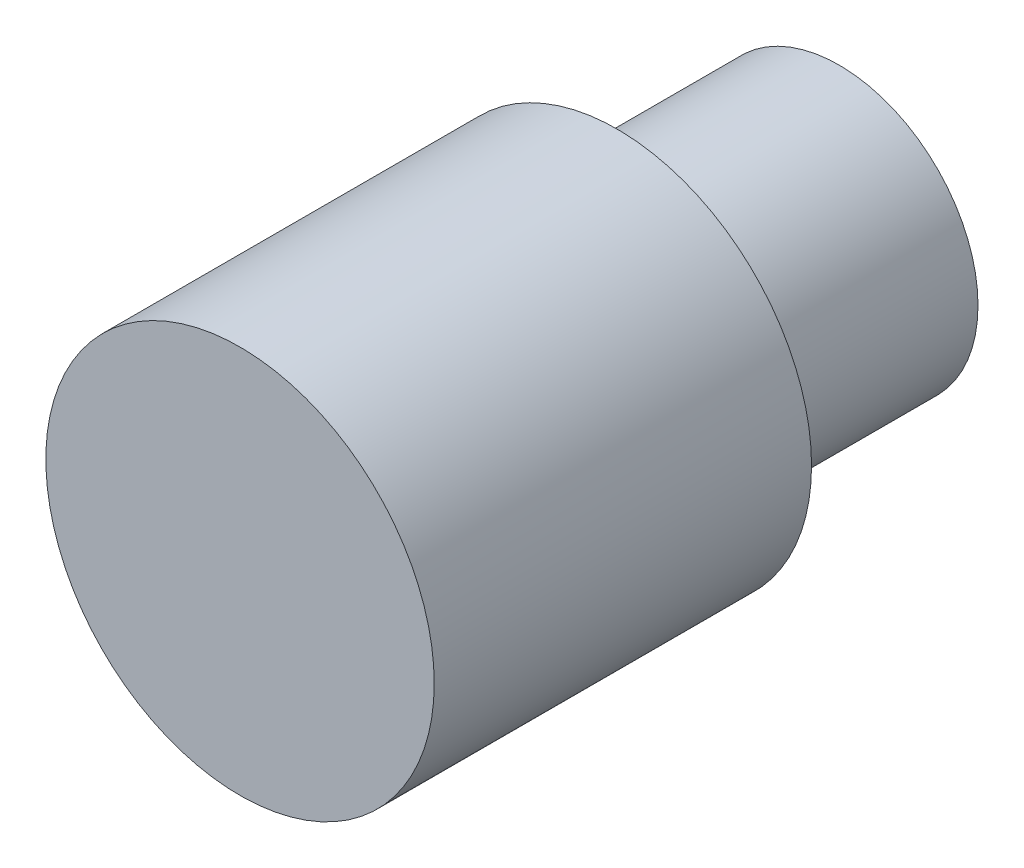
SolidWorks part; units mm, degrees
ref_plane "前视基准面" through (0, 0, 0) normal (0, 0, 1) x (1, 0, 0)
ref_plane "上视基准面" through (0, 0, 0) normal (0, 1, 0) x (1, 0, 0)
ref_plane "右视基准面" through (0, 0, 0) normal (1, 0, 0) x (0, 0, -1)
sketch "草图1" plane through (0, 0, 0) normal (0, 0, 1) x (1, 0, 0)
  circle A0 centre (0, 0) radius 12.5
  dimension "D1" = 25
extrude "凸台-拉伸1" add sketch "草图1" along normal blind 20
sketch "草图2" plane through (0, 0, 20) normal (0, 0, 1) x (1, 0, 0)
  circle A0 centre (0, 0) radius 17.5
  dimension "D1" = 35
extrude "凸台-拉伸2" add sketch "草图2" along normal blind 34
